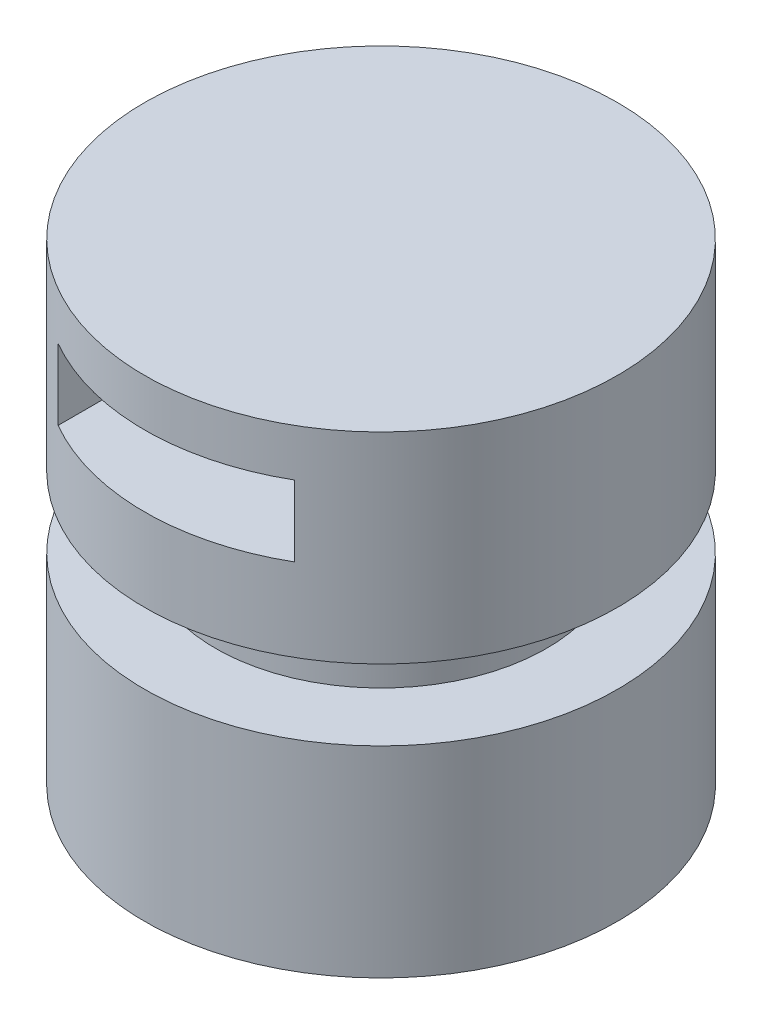
SolidWorks part; units mm, degrees
ref_plane "Front Plane" through (0, 0, 0) normal (0, 0, 1) x (1, 0, 0)
ref_plane "Top Plane" through (0, 0, 0) normal (0, 1, 0) x (1, 0, 0)
ref_plane "Right Plane" through (0, 0, 0) normal (1, 0, 0) x (0, 0, -1)
sketch "Sketch1" plane through (0, 0, 0) normal (0, 0, 1) x (1, 0, 0)
  line L1 (0, 0) -> (100, 0)
  line L2 (0, 0) -> (0, 200)
  line L3 (0, 200) -> (100, 200)
  line L4 (100, 0) -> (100, 200)
  dimension "D1" = 200
  dimension "D2" = 100
revolve "Revolve1" add sketch "Sketch1" angle 360 about L2
sketch "Sketch2" plane through (0, 0, 0) normal (1, 0, 0) x (0, 0, -1)
  line L0 (100, 0) -> (100, 200) construction
  line L1 (100, 115) -> (70, 115)
  line L2 (100, 115) -> (100, 85)
  line L3 (100, 85) -> (70, 85)
  line L4 (70, 115) -> (70, 85)
  line L5 (-100, 100) -> (100, 100) construction
  line L6 (-100, 200) -> (-100, 0) construction
  line L7 (0, -52.4218) -> (0, 234.8105) construction
  point P10 (100, 100)
  dimension "D1" = 30
revolve "Cut-Revolve1" cut sketch "Sketch2" angle 360 about L7
sketch "Sketch3" plane through (0, 0, 0) normal (0, 0, 1) x (1, 0, 0)
  line L0 (0, -83.2584) -> (0, 305.5996) construction
  line L1 (50, 150) -> (-50, 150)
  line L2 (50, 150) -> (50, 180)
  line L3 (50, 180) -> (-50, 180)
  line L4 (-50, 150) -> (-50, 180)
  line L5 (100, 200) -> (-100, 200) construction
  point P7 (0, 180)
  dimension "D1" = 100
  dimension "D2" = 30
  dimension "D3" = 20
extrude "Cut-Extrude1" cut sketch "Sketch3" against normal through all both and the other way through all
